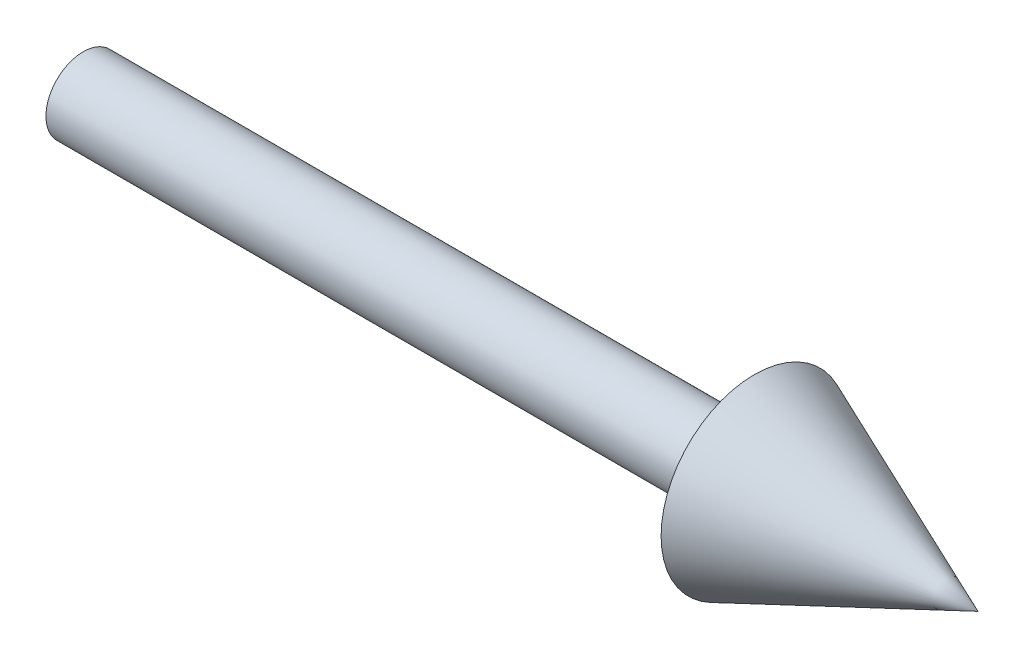
SolidWorks part; units mm, degrees
ref_plane "Front Plane" through (0, 0, 0) normal (0, 0, 1) x (1, 0, 0)
ref_plane "Top Plane" through (0, 0, 0) normal (0, 1, 0) x (1, 0, 0)
ref_plane "Right Plane" through (0, 0, 0) normal (1, 0, 0) x (0, 0, -1)
sketch "Sketch1" plane through (0, 0, 0) normal (0, 0, 1) x (1, 0, 0)
  line L0 (0, 0) -> (-10.2712, 0) construction
  line L1 (0, 0) -> (0, 5)
  line L2 (0, 5) -> (90, 5)
  line L3 (90, 5) -> (90, 12.5)
  line L4 (90, 12.5) -> (120, 0)
  line L5 (120, 0) -> (0, 0)
  dimension "D1" = 120
  dimension "D2" = 10
  dimension "D3" = 30
  dimension "D4" = 25
revolve "Revolve1" add sketch "Sketch1" angle 360 about L0
